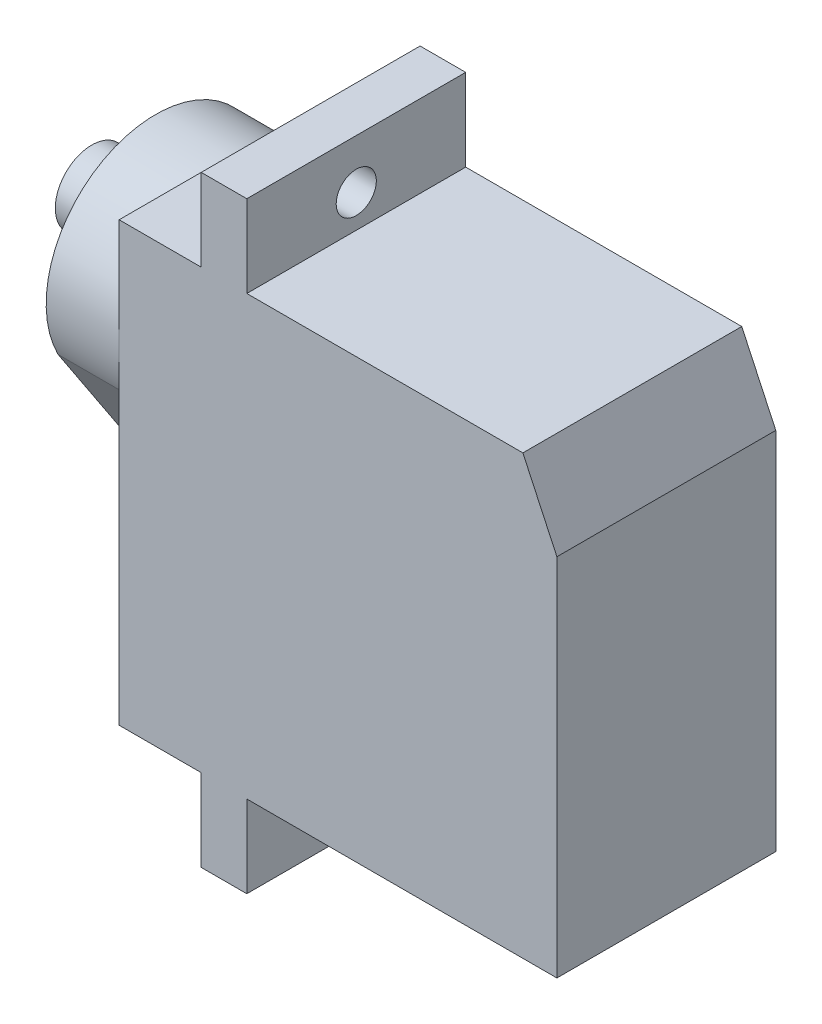
SolidWorks part; units mm, degrees
ref_plane "前视基准面" through (0, 0, 0) normal (0, 0, 1) x (1, 0, 0)
ref_plane "上视基准面" through (0, 0, 0) normal (0, 1, 0) x (1, 0, 0)
ref_plane "右视基准面" through (0, 0, 0) normal (1, 0, 0) x (0, 0, -1)
sketch "草图1" plane through (0, 0, 0) normal (0, 0, 1) x (1, 0, 0)
  line L0 (7, 24) -> (7, 28.5)
  line L1 (0, 0) -> (4.5, 0)
  line L2 (0, 0) -> (0, 24)
  line L3 (0, 24) -> (4.5, 24)
  line L4 (24, 0) -> (24, 24)
  line L5 (7, -4.5) -> (4.5, -4.5)
  line L6 (7, -4.5) -> (7, 0)
  line L7 (7, 28.5) -> (4.5, 28.5)
  line L8 (4.5, -4.5) -> (4.5, 0)
  line L9 (4.5, 24) -> (4.5, 28.5)
  line L10 (7, 0) -> (24, 0)
  line L11 (7, 24) -> (24, 24)
  point P4 (3.85, 11.5)
  dimension "D1" = 24
  dimension "D2" = 24
  dimension "D3" = 11.5
  dimension "D4" = 17
  dimension "D5" = 2.5
  dimension "D6" = 33
extrude "凸台-拉伸1" add sketch "草图1" along normal blind 12
sketch "草图3" plane through (4.5, 0, 0) normal (-1, 0, 0) x (0, 0, 1)
  line L3 (17.1701, 12) -> (-7.9355, 12) construction
  line L5 (12, 24) -> (12, 0) construction
  line L9 (0, 28.5) -> (0, 24) construction
  circle A0 centre (6, 25.8) radius 1.1
  circle A1 centre (6, -1.8) radius 1.1
  point P3 (6, 24)
  point P6 (12, 12)
  dimension "D2" = 27.6
  dimension "D1" = 6
extrude "切除-拉伸1" cut sketch "草图3" against normal through all
sketch "草图10" plane through (0, 0, 0) normal (-1, 0, 0) x (0, 0, 1)
  line L1 (0.9848, 14.7063) -> (5.288, 8.154)
  line L2 (6.7143, 8.2627) -> (11.3475, 15.2789)
  line L4 (12, 24) -> (12, 0) construction
  line L5 (0, 24) -> (0, 0) construction
  line L6 (12, 24) -> (0, 24) construction
  line L7 (6, 18) -> (6, 4.0017) construction
  arc A1 (5.288, 8.154) -> (6.7143, 8.2627) centre (6, 8.2232) ccw
  arc A4 (11.3475, 15.2789) -> (0.9848, 14.7063) centre (6, 18) ccw
extrude "凸台-拉伸2" add sketch "草图10" along normal blind 4
sketch "草图11" plane through (-4, 0, 0) normal (-1, 0, 0) x (0, 0, 1)
  line L0 (6, 18) -> (6, 4.0017) construction
  circle A0 centre (6, 18.8) radius 2
  circle A1 centre (6, 25.8) radius 1.1 construction
  dimension "D1" = 7
extrude "凸台-拉伸4" add sketch "草图11" along normal blind 3.5
chamfer "倒角1" distance 4 angle 25 1 edges at (24, 24, 6)
